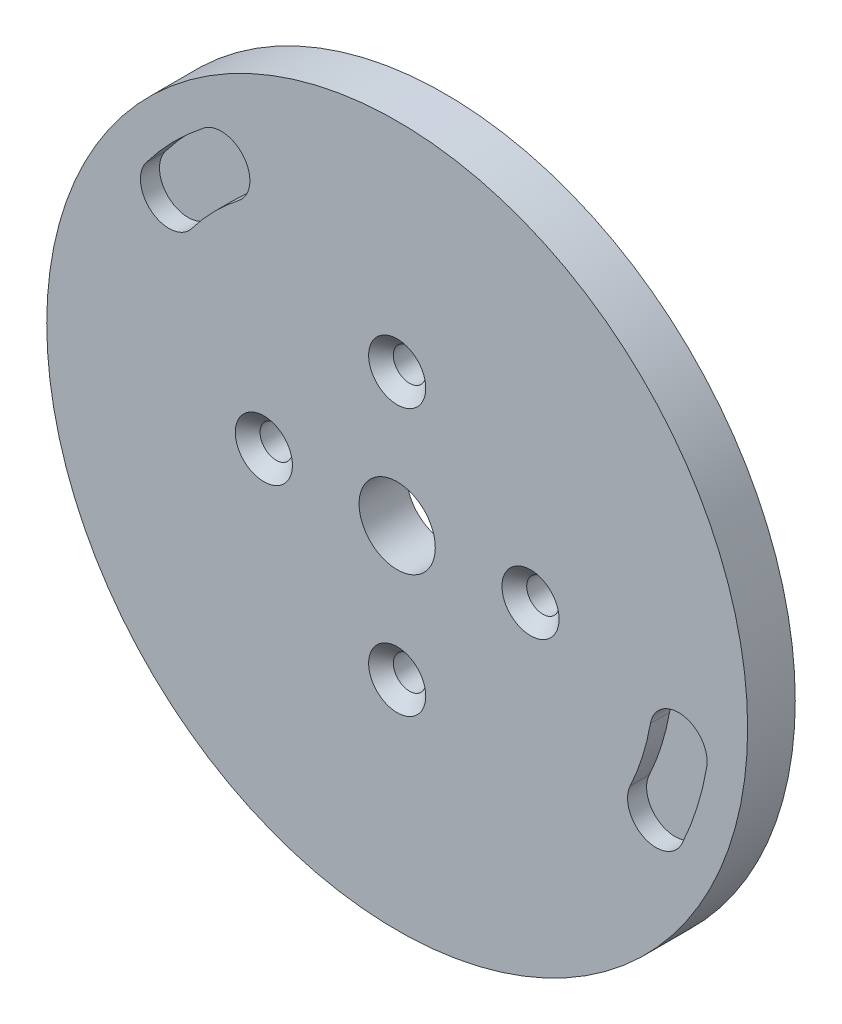
SolidWorks part; units mm, degrees
ref_plane "Front Plane" through (0, 0, 0) normal (0, 0, 1) x (1, 0, 0)
ref_plane "Top Plane" through (0, 0, 0) normal (0, 1, 0) x (1, 0, 0)
ref_plane "Right Plane" through (0, 0, 0) normal (1, 0, 0) x (0, 0, -1)
sketch "Sketch1" plane through (0, 0, 0) normal (0, 0, 1) x (1, 0, 0)
  circle A0 centre (0, 0) radius 36.8
extrude "Boss-Extrude1" add sketch "Sketch1" along normal blind 5
sketch "Sketch2" plane through (0, 0, 5) normal (0, 0, 1) x (1, 0, 0)
  circle A0 centre (0, 0) radius 4
extrude "Cut-Extrude1" cut sketch "Sketch2" against normal up to next
sketch "Sketch3" plane through (0, 0, 5) normal (0, 0, 1) x (1, 0, 0)
  arc A0 (24.4703, -11.4107) -> (26.5898, -4.6885) centre (0, 0) ccw
  arc A1 (29.9082, -13.9464) -> (32.4987, -5.7304) centre (0, 0) ccw
  arc A2 (32.4987, -5.7304) -> (26.5898, -4.6885) centre (29.5442, -5.2094) ccw
  arc A3 (24.4703, -11.4107) -> (29.9082, -13.9464) centre (27.1892, -12.6785) ccw
extrude "Cut-Extrude2" cut sketch "Sketch3" against normal blind 2
sketch "Sketch4" plane through (0, 0, 5) normal (0, 0, 1) x (1, 0, 0)
  arc A0 (-20.3168, 26.0044) -> (-26.355, 19.8599) centre (0, 0) ccw
  arc A1 (-16.6229, 21.2763) -> (-21.5632, 16.249) centre (0, 0) ccw
  arc A2 (-26.355, 19.8599) -> (-21.5632, 16.249) centre (-23.9591, 18.0545) ccw
  arc A3 (-16.6229, 21.2763) -> (-20.3168, 26.0044) centre (-18.4698, 23.6403) ccw
extrude "Cut-Extrude3" cut sketch "Sketch4" against normal blind 2
sketch "Sketch5" plane through (0, 0, 5) normal (0, 0, 1) x (1, 0, 0)
  point P0 (0, 14)
  point P2 (14, 0)
  point P4 (0, -14)
  point P6 (-14, 0)
  point P9 (0, 0)
  point P10 (0, 0)
  point P11 (0, 0)
  point P12 (0, 0)
hole_wizard "CSK for M3 Flat Countersunk Head Screw1" positions "Sketch5" profile "Sketch6" countersink size "M3" standard "JIS"
sketch "Sketch6" plane through (0, 14, 5) normal (1, 0, 0) x (0, -1, 0)
  line L0 (0, 0) -> (0, 10.0215)
  line L1 (0, 10.0215) -> (1.7, 9)
  line L2 (1.7, 9) -> (1.7, 1.3)
  line L3 (1.7, 1.3) -> (3, 0)
  line L5 (3, 0) -> (0, 0)
  line L6 (-1.7, 1.3) -> (-3, 0) construction
  line L10 (0, 10.0215) -> (-1.7, 9) construction
  line L11 (0, -6.35) -> (0, 107.95) construction
  dimension "Hole Dia." = 3.4
  dimension "Hole Depth" = 9
  dimension "Near C'Sink Dia." = 6
  dimension "Near C'Sink Angle" = 90
  dimension "Drill Angle" = 118
